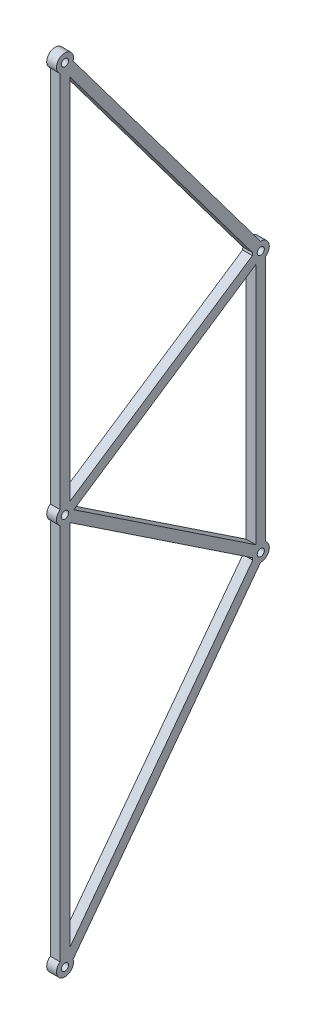
SolidWorks part; units mm, degrees
material "ASTM A500 Grade C"
ref_plane "Front Plane" through (0, 0, 0) normal (1, 0, 0) x (0, 1, 0)
ref_plane "Top Plane" through (0, 0, 0) normal (0, 0, 1) x (0, 1, 0)
ref_plane "Right Plane" through (0, 0, 0) normal (0, 1, 0) x (-1, 0, 0)
sketch "Sketch2" plane through (0, 0, 0) normal (1, 0, 0) x (0, 1, 0)
  line L0 (0, 0) -> (583.677, 0) construction
  line L1 (0, 0) -> (0, 300) construction
  line L2 (0, 300) -> (400, 0) construction
  line L3 (400, 0) -> (800, 0) construction
  line L4 (800, 0) -> (1200, 300) construction
  line L5 (1200, 300) -> (600, 300) construction
  line L6 (600, 300) -> (0, 300) construction
  line L7 (400, 0) -> (600, 300) construction
  line L8 (800, 0) -> (600, 300) construction
  line L9 (600, 307.5) -> (-22.5, 307.5)
  line L10 (-22.5, 307.5) -> (395.5, -6)
  line L11 (414.0139, 7.5) -> (600, 286.4792)
  line L12 (804.5, -6) -> (1222.5, 307.5)
  line L13 (1222.5, 307.5) -> (600, 307.5)
  line L14 (801.8426, 10.7569) -> (614.0139, 292.5)
  line L15 (400, -7.5) -> (800, -7.5)
  line L16 (585.9861, 292.5) -> (22.5, 292.5)
  line L17 (22.5, 292.5) -> (398.1574, 10.7569)
  line L18 (398.1574, 10.7569) -> (585.9861, 292.5)
  line L19 (801.8426, 10.7569) -> (1177.5, 292.5)
  line L20 (1177.5, 292.5) -> (614.0139, 292.5)
  line L21 (785.9861, 7.5) -> (600, 286.4792)
  line L22 (414.0139, 7.5) -> (785.9861, 7.5)
  line L23 (393.7596, 4.1603) -> (593.7596, 304.1603) construction
  line L24 (400, 7.5) -> (800, 7.5) construction
  line L25 (406.2404, -4.1603) -> (606.2404, 295.8397) construction
  line L26 (22.5, 292.5) -> (404.5, 6) construction
  line L27 (600, 292.5) -> (22.5, 292.5) construction
  line L28 (793.7596, -4.1603) -> (593.7596, 295.8397) construction
  line L29 (1177.5, 292.5) -> (600, 292.5) construction
  line L30 (806.2404, 4.1603) -> (606.2404, 304.1603) construction
  line L31 (795.5, 6) -> (1177.5, 292.5) construction
  arc A0 (395.5, -6) -> (400, -7.5) centre (400, 0) ccw
  arc A1 (800, -7.5) -> (804.5, -6) centre (800, 0) ccw
  point P3 (600, 300)
  point P5 (0, 300)
  point P6 (1200, 300)
  point P7 (800, 0)
  point P8 (400, 0)
  dimension "D1" = 300
  dimension "D2" = 600
  dimension "D3" = 600
  dimension "D4" = 400
  dimension "D5" = 400
  dimension "D6" = 7.5
  dimension "D7" = 7.5
extrude "Boss-Extrude1" add sketch "Sketch2" along normal blind 15
sketch "Sketch3" plane through (15, 0, 0) normal (1, 0, 0) x (0, 1, 0)
  circle A0 centre (400, 0) radius 13
  circle A1 centre (0, 300) radius 13
  circle A2 centre (600, 300) radius 13
  circle A3 centre (1200, 300) radius 13
  circle A4 centre (800, 0) radius 13
  dimension "D1" = 26
  dimension "D2" = 26
  dimension "D3" = 26
  dimension "D4" = 26
  dimension "D5" = 26
extrude "Boss-Extrude2" add sketch "Sketch3" against normal blind 15 contours A3 | A2 | A1 | A0 | A4
sketch "Sketch4" plane through (15, 0, 0) normal (1, 0, 0) x (0, 1, 0)
  line L0 (-10.6184, 307.5) -> (-22.5, 307.5)
  line L1 (-22.5, 307.5) -> (-12.9947, 300.371)
  line L2 (1210.6184, 307.5) -> (1222.5, 307.5)
  line L3 (1222.5, 307.5) -> (1212.9947, 300.371)
  arc A0 (-12.9947, 300.371) -> (-10.6184, 307.5) centre (0, 300) cw
  arc A1 (1210.6184, 307.5) -> (1212.9947, 300.371) centre (1200, 300) cw
  dimension "D1" = 13
  dimension "D2" = 13
extrude "Cut-Extrude1" cut sketch "Sketch4" against normal blind 15
sketch "Sketch5" plane through (15, 0, 0) normal (1, 0, 0) x (0, 1, 0)
  circle A0 centre (0, 300) radius 5.5
  circle A1 centre (600, 300) radius 5.5
  circle A2 centre (1200, 300) radius 5.5
  circle A3 centre (800, 0) radius 5.5
  circle A4 centre (400, 0) radius 5.5
  dimension "D1" = 11
  dimension "D2" = 11
  dimension "D3" = 11
  dimension "D4" = 11
  dimension "D5" = 11
extrude "Cut-Extrude2" cut sketch "Sketch5" against normal blind 15
